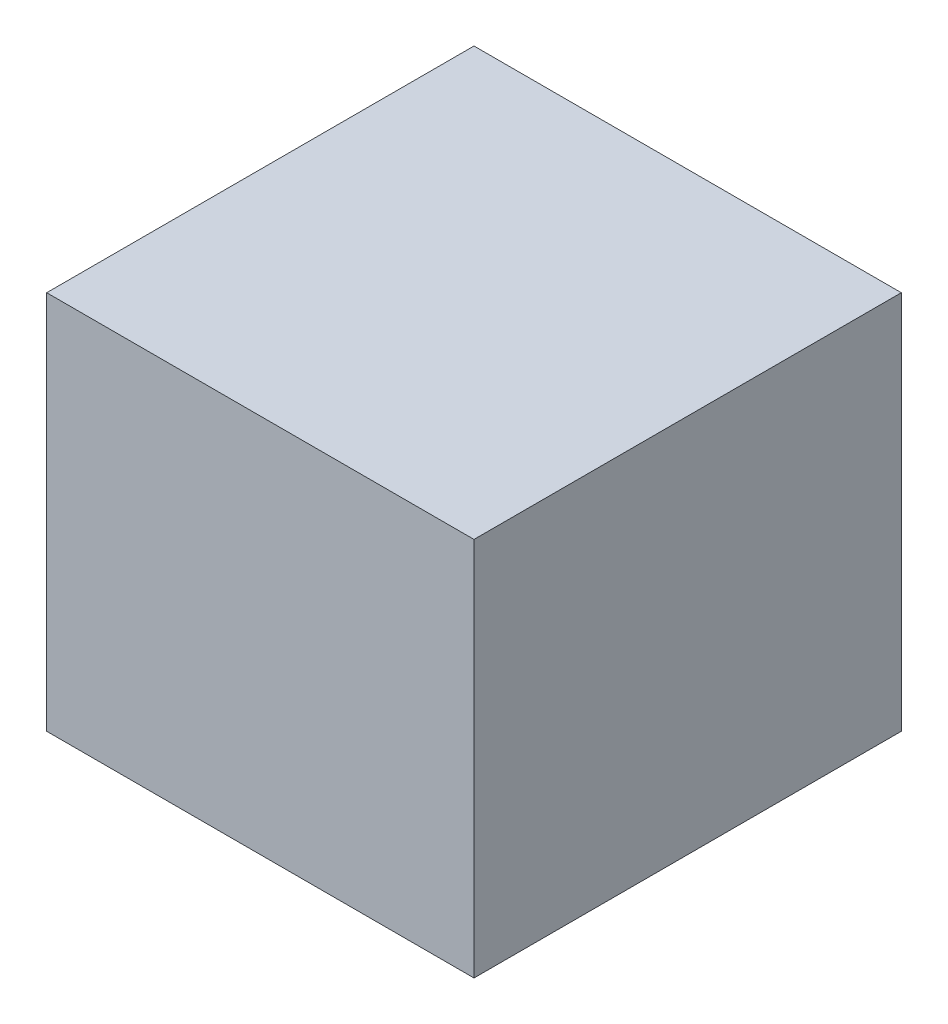
SolidWorks part; units mm, degrees
ref_plane "Přední rovina" through (0, 0, 0) normal (0, 0, 1) x (1, 0, 0)
ref_plane "Horní rovina" through (0, 0, 0) normal (0, 1, 0) x (1, 0, 0)
ref_plane "Pravá rovina" through (0, 0, 0) normal (1, 0, 0) x (0, 0, -1)
sketch "Skica1" plane through (0, 0, 0) normal (0, 1, 0) x (1, 0, 0)
  line L0 (0, 0) -> (180, 0)
  line L1 (180, 0) -> (180, 180)
  line L2 (180, 180) -> (0, 180)
  line L3 (0, 180) -> (0, 0)
  dimension "D1" = 180
  dimension "D2" = 180
extrude "Přidat vysunutím1" add sketch "Skica1" along normal blind 160
